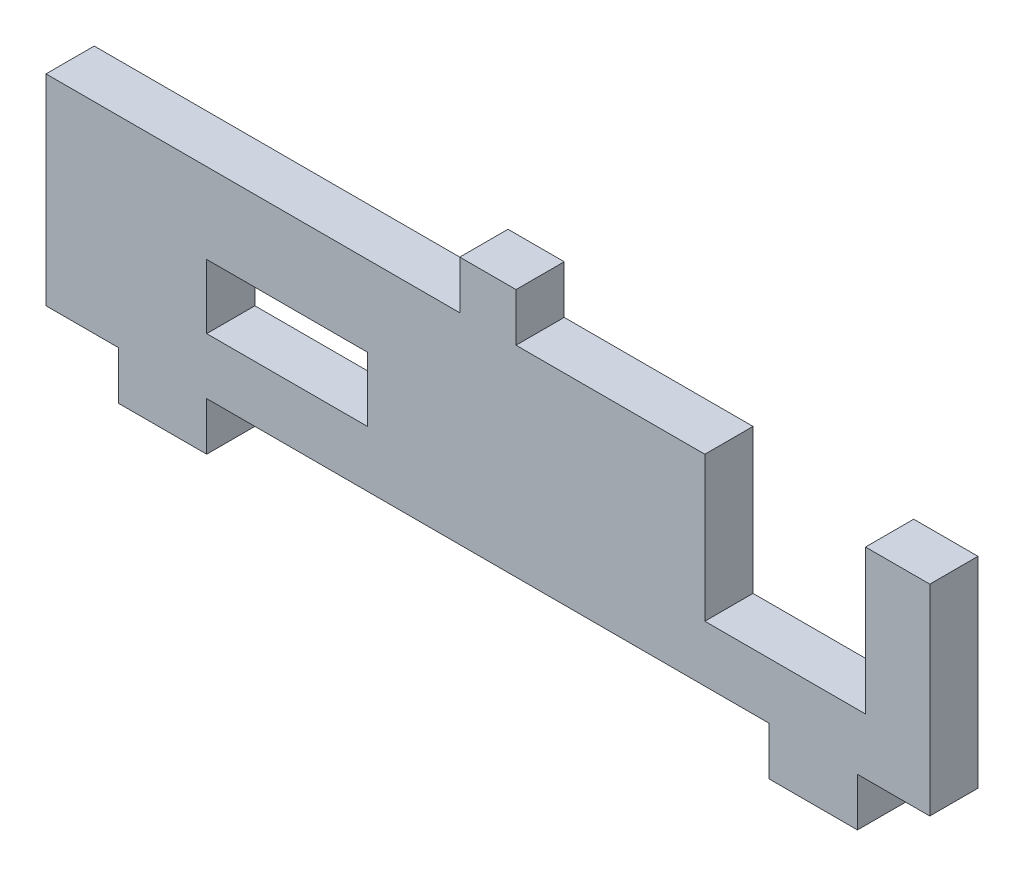
SolidWorks part; units mm, degrees
ref_plane "Alzado" through (0, 0, 0) normal (0, 0, 1) x (1, 0, 0)
ref_plane "Planta" through (0, 0, 0) normal (0, 1, 0) x (1, 0, 0)
ref_plane "Vista lateral" through (0, 0, 0) normal (1, 0, 0) x (0, 0, -1)
sketch "Croquis1" plane through (0, 0, 0) normal (0, 0, 1) x (1, 0, 0)
  line L0 (-17.5, -6.25) -> (17.5, -6.25)
  line L1 (-27.5, -6.25) -> (-23, -6.25)
  line L2 (-27.5, -6.25) -> (-27.5, 6.25)
  line L3 (-27.5, 6.25) -> (-1.75, 6.25)
  line L4 (27.5, -6.25) -> (27.5, 6.25)
  line L5 (-27.5, -6.25) -> (27.5, 6.25) construction
  line L6 (-27.5, 6.25) -> (27.5, -6.25) construction
  line L7 (23.5, 6.25) -> (27.5, 6.25)
  line L8 (-1.75, 6.25) -> (-1.75, 9.25)
  line L9 (-1.75, 9.25) -> (1.75, 9.25)
  line L10 (1.75, 6.25) -> (1.75, 9.25)
  line L11 (23, -6.25) -> (27.5, -6.25)
  line L12 (-23, -6.25) -> (-23, -9.25)
  line L13 (-23, -9.25) -> (-17.5, -9.25)
  line L14 (-17.5, -6.25) -> (-17.5, -9.25)
  line L15 (1.75, 6.25) -> (13.5, 6.25)
  line L16 (17.5, -6.25) -> (17.5, -9.25)
  line L17 (17.5, -9.25) -> (23, -9.25)
  line L18 (23, -6.25) -> (23, -9.25)
  line L20 (13.5, 6.25) -> (13.5, -2.75)
  line L21 (13.5, -2.75) -> (23.5, -2.75)
  line L22 (23.5, 6.25) -> (23.5, -2.75)
  line L23 (-17.5, 1.25) -> (-7.5, 1.25)
  line L24 (-17.5, 1.25) -> (-17.5, -2.75)
  line L25 (-17.5, -2.75) -> (-7.5, -2.75)
  line L26 (-7.5, 1.25) -> (-7.5, -2.75)
  point P0 (0, 0)
  point P18 (0, 9.25)
  dimension "D1" = 55
  dimension "D2" = 12.5
  dimension "D3" = 5.5
  dimension "D4" = 5.5
  dimension "D5" = 35
  dimension "D6" = 4.5
  dimension "D7" = 3
  dimension "D8" = 3.5
  dimension "D9" = 3
  dimension "D10" = 10
  dimension "D11" = 4
  dimension "D12" = 9
  dimension "D13" = 10
  dimension "D14" = 10
  dimension "D15" = 4
extrude "Saliente-Extruir2" add sketch "Croquis1" along normal blind 3
